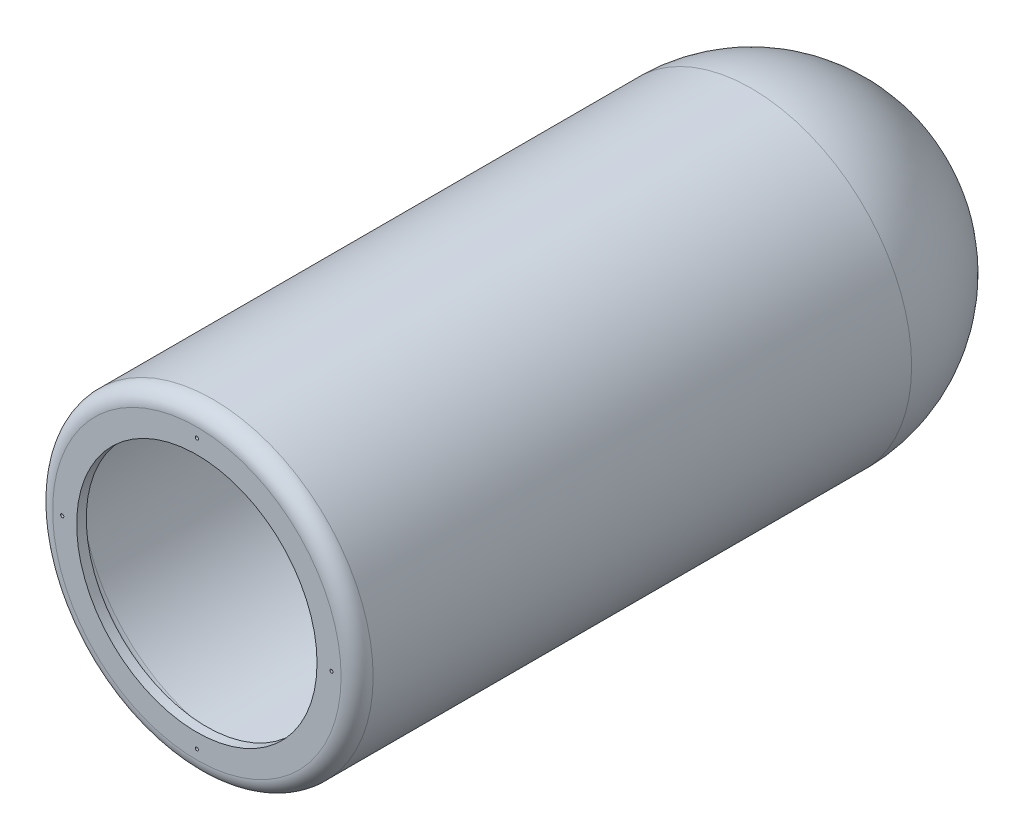
SolidWorks part; units mm, degrees
ref_plane "Front" through (0, 0, 0) normal (0, 0, 1) x (1, 0, 0)
ref_plane "Top" through (0, 0, 0) normal (0, 1, 0) x (1, 0, 0)
ref_plane "Right" through (0, 0, 0) normal (1, 0, 0) x (0, 0, -1)
sketch "Sketch1" plane through (0, 0, 0) normal (0, 0, 1) x (1, 0, 0)
  circle A0 centre (0, 0) radius 50
  dimension "D1" = 100
extrude "Boss-Extrude1" add sketch "Sketch1" along normal blind 3
sketch "Sketch2" plane through (0, 0, 3) normal (0, 0, 1) x (1, 0, 0)
  circle A0 centre (0, 0) radius 37.5
  dimension "D1" = 75
extrude "Cut-Extrude1" cut sketch "Sketch2" against normal blind 4
sketch "Sketch3" plane through (0, 0, 0) normal (0, 0, -1) x (-1, 0, 0)
  circle A0 centre (0, 0) radius 50
  circle A1 centre (0, 0) radius 47
  dimension "D1" = 3
extrude "Boss-Extrude2" add sketch "Sketch3" along normal blind 170
fillet "Fillet1" radius 8 1 edges at (-47, 0, 0)
sketch "Sketch4" plane through (0, 0, -170) normal (0, 0, -1) x (-1, 0, 0)
  line L0 (-47, 0) -> (99.5143, 0) construction
  line L1 (50, 0) -> (47, 0)
  line L2 (-47, 0) -> (-50, 0)
  arc A0 (50, 0) -> (-50, 0) centre (0, 0) ccw
  arc A1 (47, 0) -> (-47, 0) centre (0, 0) ccw
revolve "Revolve4" add sketch "Sketch4" angle 180 about L0
sketch "Sketch5" plane through (0, 0, 3) normal (0, 0, 1) x (1, 0, 0)
  circle A0 centre (0, 0) radius 42 construction
  circle A1 centre (0, -42) radius 0.5
  circle A2 centre (-42, 0) radius 0.5
  circle A3 centre (0, 42) radius 0.5
  circle A4 centre (42, 0) radius 0.5
  point P14 (0, 0)
  dimension "D1" = 84
  dimension "D2" = 1
  dimension "D3" = 4
extrude "Cut-Extrude2" cut sketch "Sketch5" against normal blind 3
sketch "Sketch6" plane through (0, 0, 3) normal (0, 0, 1) x (1, 0, 0)
  circle A0 centre (0, 0) radius 1.5
  dimension "D1" = 3
extrude "Cut-Extrude3" cut sketch "Sketch6" against normal through all
fillet "Fillet2" radius 5 1 edges at (50, 0, 3)
